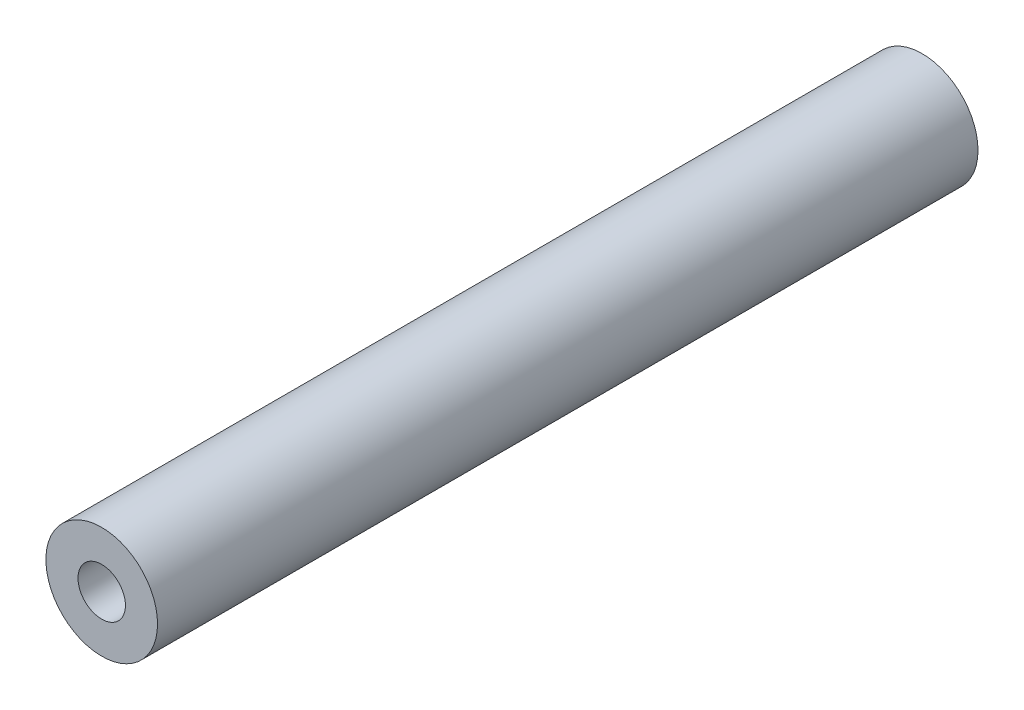
SolidWorks part; units mm, degrees
material "AISI 304"
ref_plane "Plano frontal" through (0, 0, 0) normal (0, 0, 1) x (1, 0, 0)
ref_plane "Plano superior" through (0, 0, 0) normal (0, 1, 0) x (1, 0, 0)
ref_plane "Plano direito" through (0, 0, 0) normal (1, 0, 0) x (0, 0, -1)
sketch "Esboço1" plane through (0, 0, 0) normal (0, 0, 1) x (1, 0, 0)
  circle A0 centre (0, 0) radius 4.25
  circle A1 centre (0, 0) radius 10
  dimension "D1" = 8.5
  dimension "D2" = 20
extrude "Ressalto-extrusão1" add sketch "Esboço1" along normal mid plane 147
